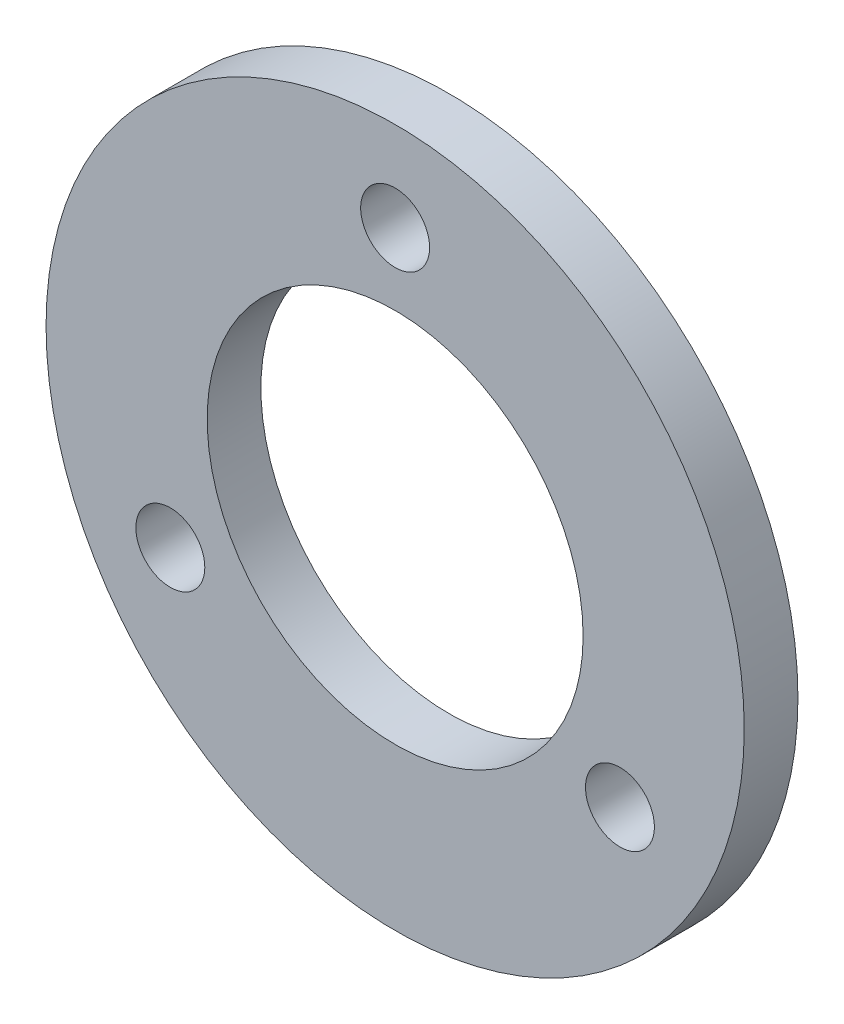
SolidWorks part; units mm, degrees
ref_plane "Plan de face" through (0, 0, 0) normal (0, 0, 1) x (1, 0, 0)
ref_plane "Plan de dessus" through (0, 0, 0) normal (0, 1, 0) x (1, 0, 0)
ref_plane "Plan de droite" through (0, 0, 0) normal (1, 0, 0) x (0, 0, -1)
sketch "Esquisse1" plane through (0, 0, 0) normal (0, 0, 1) x (1, 0, 0)
  circle A0 centre (0, 0) radius 10.5
  circle A1 centre (0, 0) radius 19.5
  circle A2 centre (12.5574, -7.25) radius 1.925
  circle A3 centre (-12.5574, -7.25) radius 1.925
  circle A5 centre (0, 14.5) radius 1.925
  point P9 (0, 0)
  dimension "D1" = 21
  dimension "D2" = 3.85
  dimension "D3" = 14.5
  dimension "D4" = 39
  dimension "D5" = 3
extrude "Boss.-Extru.1" add sketch "Esquisse1" along normal blind 3
